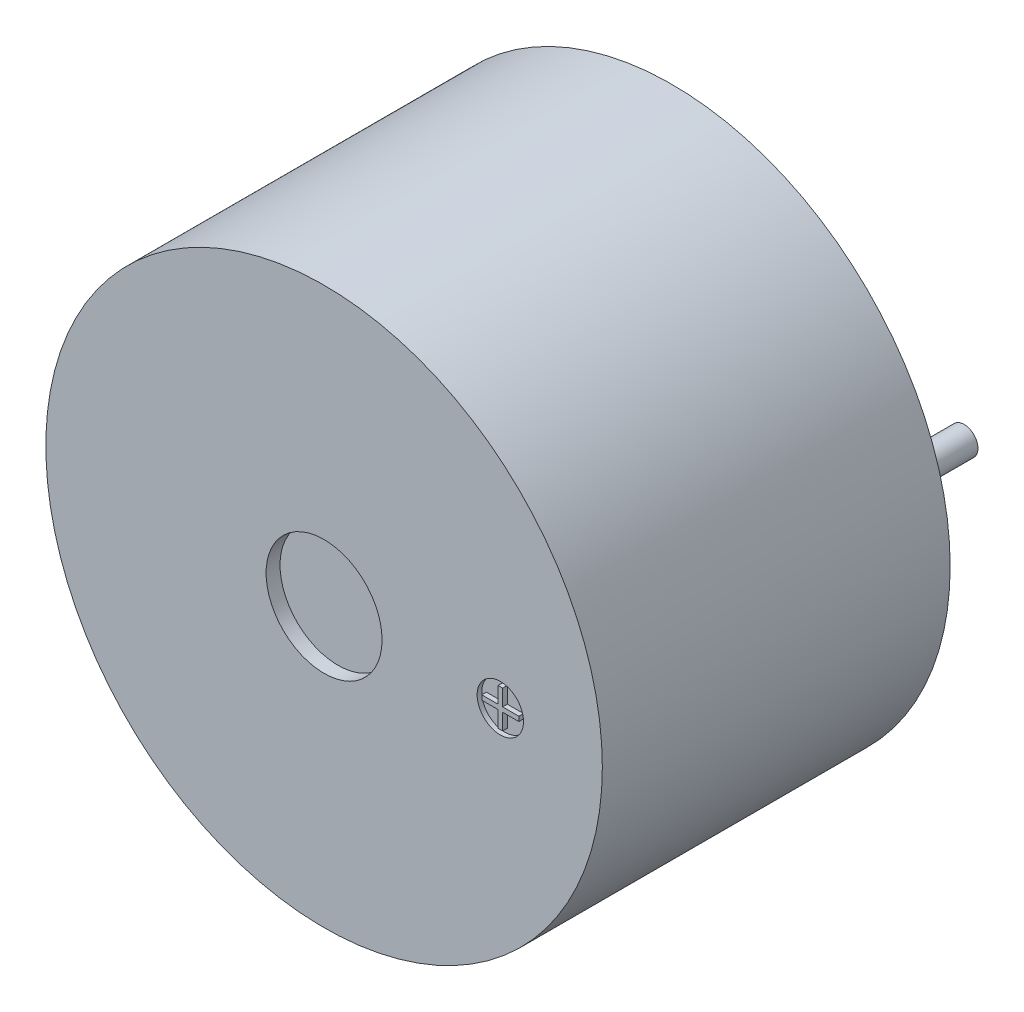
SolidWorks part; units mm, degrees
ref_plane "Front Plane" through (0, 0, 0) normal (0, 0, 1) x (1, 0, 0)
ref_plane "Top Plane" through (0, 0, 0) normal (0, 1, 0) x (1, 0, 0)
ref_plane "Right Plane" through (0, 0, 0) normal (1, 0, 0) x (0, 0, -1)
sketch "Sketch1" plane through (0, 0, 0) normal (0, 0, 1) x (1, 0, 0)
  circle A0 centre (0, 0) radius 6
  dimension "D1" = 12
extrude "Boss-Extrude1" add sketch "Sketch1" along normal blind 7.5
sketch "Sketch2" plane through (0, 0, 0) normal (0, 0, -1) x (-1, 0, 0)
  line L0 (3.8, 0) -> (-3.8, 0) construction
  circle A0 centre (3.8, 0) radius 0.3
  circle A1 centre (-3.8, 0) radius 0.3
  point P4 (0, 0)
  dimension "D1" = 0.6
  dimension "D2" = 7.6
extrude "Boss-Extrude2" add sketch "Sketch2" along normal blind 2.5
sketch "Sketch3" plane through (0, 0, 7.5) normal (0, 0, 1) x (1, 0, 0)
  circle A0 centre (0, 0) radius 1.25
  dimension "D1" = 2.5
extrude "Cut-Extrude1" cut sketch "Sketch3" against normal blind 1.8
sketch "Sketch4" plane through (0, 0, 5.7) normal (0, 0, 1) x (1, 0, 0)
  circle A0 centre (0, 0) radius 5.7
  circle A1 centre (0, 0) radius 6 construction
  dimension "D1" = 0.3
extrude "Cut-Extrude2" cut sketch "Sketch4" along normal offset from surface (1.5 mm away) 0.3 up to face at (1.25, 0, 7.5)
sketch "Sketch5" plane through (0, 0, 7.5) normal (0, 0, 1) x (1, 0, 0)
  line L0 (0, 0) -> (6, 0) construction
  circle A0 centre (3.8, 0) radius 0.5
  circle A1 centre (0, 0) radius 6 construction
  point P8 (0, 0)
  point P9 (3, 0)
  dimension "D1" = 1
  dimension "D2" = 0.8
extrude "Cut-Extrude3" cut sketch "Sketch5" against normal blind 0.1
sketch "Sketch6" plane through (0, 0, 7.4) normal (0, 0, 1) x (1, 0, 0)
  line L1 (3.75, -0.4) -> (3.85, -0.4)
  line L2 (3.75, -0.4) -> (3.75, 0.4)
  line L3 (3.75, 0.4) -> (3.85, 0.4)
  line L4 (3.85, -0.4) -> (3.85, 0.4)
  line L5 (3.75, -0.4) -> (3.85, 0.4) construction
  line L6 (3.75, 0.4) -> (3.85, -0.4) construction
  line L7 (3.4, 0.05) -> (4.2, 0.05)
  line L8 (3.4, 0.05) -> (3.4, -0.05)
  line L9 (3.4, -0.05) -> (4.2, -0.05)
  line L10 (4.2, 0.05) -> (4.2, -0.05)
  line L11 (3.4, 0.05) -> (4.2, -0.05) construction
  line L12 (3.4, -0.05) -> (4.2, 0.05) construction
  circle A0 centre (3.8, 0) radius 0.5 construction
  point P0 (3.8, 0)
  point P5 (3.8, 0)
  point P10 (3.8197, 0.0582)
  point P11 (0, 0)
  point P14 (4.2173, -0.0378)
  dimension "D1" = 0.8
  dimension "D2" = 0.1
extrude "Boss-Extrude3" add sketch "Sketch6" along normal up to surface (0.1 mm away) contours L10 L7 L4 L9 | L8 L9 L2 L7 | L2 L7 L4 L3 | L9 L2 L1 L4 | L2 L9 L4 L7 up to face at (4.3, 0, 7.5)
